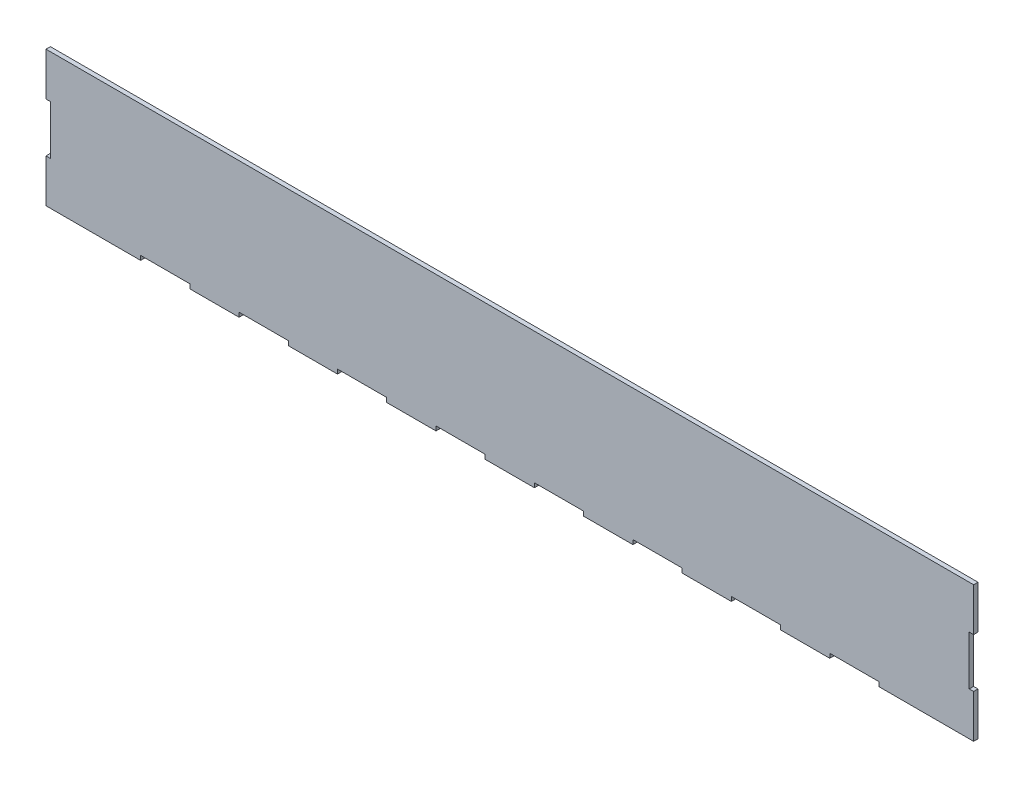
SolidWorks part; units mm, degrees
ref_plane "Front Plane" through (0, 0, 0) normal (0, 0, 1) x (1, 0, 0)
ref_plane "Top Plane" through (0, 0, 0) normal (0, 1, 0) x (1, 0, 0)
ref_plane "Right Plane" through (0, 0, 0) normal (1, 0, 0) x (0, 0, -1)
sketch "Model" plane through (0, 0, 0) normal (0, 0, 1) x (1, 0, 0)
  line L0 (0, 96) -> (0, 66.375)
  line L1 (0, 66.375) -> (3, 66.375)
  line L2 (3, 66.375) -> (3, 32.625)
  line L3 (3, 32.625) -> (0, 32.625)
  line L4 (0, 32.625) -> (0, 3)
  line L5 (0, 3) -> (64.875, 3)
  line L6 (64.875, 3) -> (64.875, 6)
  line L7 (64.875, 6) -> (98.625, 6)
  line L8 (98.625, 6) -> (98.625, 3)
  line L9 (98.625, 3) -> (132.375, 3)
  line L10 (132.375, 3) -> (132.375, 6)
  line L11 (132.375, 6) -> (166.125, 6)
  line L12 (166.125, 6) -> (166.125, 3)
  line L13 (166.125, 3) -> (199.875, 3)
  line L14 (199.875, 3) -> (199.875, 6)
  line L15 (199.875, 6) -> (233.625, 6)
  line L16 (233.625, 6) -> (233.625, 3)
  line L17 (233.625, 3) -> (267.375, 3)
  line L18 (267.375, 3) -> (267.375, 6)
  line L19 (267.375, 6) -> (301.125, 6)
  line L20 (301.125, 6) -> (301.125, 3)
  line L21 (301.125, 3) -> (334.875, 3)
  line L22 (334.875, 3) -> (334.875, 6)
  line L23 (334.875, 6) -> (368.625, 6)
  line L24 (368.625, 6) -> (368.625, 3)
  line L25 (368.625, 3) -> (402.375, 3)
  line L26 (402.375, 3) -> (402.375, 6)
  line L27 (402.375, 6) -> (436.125, 6)
  line L28 (436.125, 6) -> (436.125, 3)
  line L29 (436.125, 3) -> (469.875, 3)
  line L30 (469.875, 3) -> (469.875, 6)
  line L31 (469.875, 6) -> (503.625, 6)
  line L32 (503.625, 6) -> (503.625, 3)
  line L33 (503.625, 3) -> (537.375, 3)
  line L34 (537.375, 3) -> (537.375, 6)
  line L35 (537.375, 6) -> (571.125, 6)
  line L36 (571.125, 6) -> (571.125, 3)
  line L37 (571.125, 3) -> (604.875, 3)
  line L38 (604.875, 3) -> (636, 3)
  line L39 (636, 3) -> (636, 32.625)
  line L40 (636, 32.625) -> (633, 32.625)
  line L41 (633, 32.625) -> (633, 66.375)
  line L42 (633, 66.375) -> (636, 66.375)
  line L43 (636, 66.375) -> (636, 96)
  line L44 (636, 96) -> (0, 96)
extrude "Boss-Extrude1" add sketch "Model" along normal blind 3
